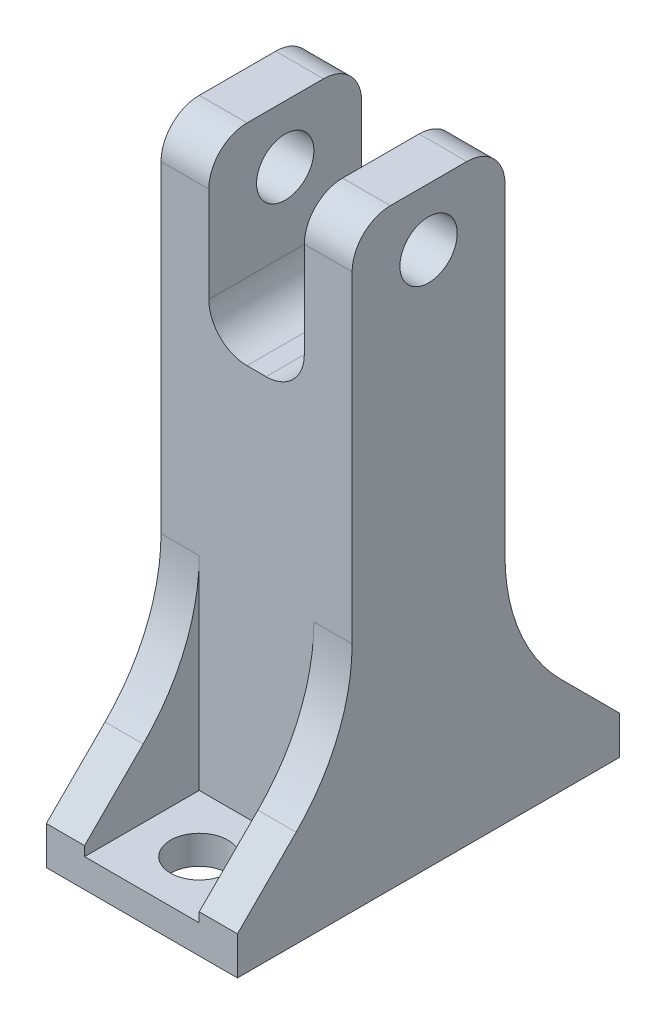
SolidWorks part; units mm, degrees
ref_plane "Front Plane" through (0, 0, 0) normal (0, 0, 1) x (1, 0, 0)
ref_plane "Top Plane" through (0, 0, 0) normal (0, 1, 0) x (1, 0, 0)
ref_plane "Right Plane" through (0, 0, 0) normal (1, 0, 0) x (0, 0, -1)
sketch "Sketch1" plane through (0, 0, 0) normal (0, 0, 1) x (1, 0, 0)
  line L0 (2.5, 15.5) -> (5, 15.5)
  line L1 (-5, -15.5) -> (5, -15.5)
  line L2 (-5, -15.5) -> (-5, 15.5)
  line L3 (-5, 15.5) -> (-2.5, 15.5)
  line L4 (5, -15.5) -> (5, 15.5)
  line L5 (-5, -15.5) -> (5, 15.5) construction
  line L6 (-5, 15.5) -> (5, -15.5) construction
  line L7 (-2.5, 6.5) -> (2.5, 6.5)
  line L8 (-2.5, 6.5) -> (-2.5, 15.5)
  line L10 (2.5, 6.5) -> (2.5, 15.5)
  line L11 (-2.5, 6.5) -> (2.5, 15.5) construction
  line L12 (-2.5, 15.5) -> (2.5, 6.5) construction
  point P0 (0, 0)
  point P5 (0, 11)
  dimension "D1" = 31
  dimension "D2" = 10
  dimension "D3" = 9
  dimension "D4" = 5
extrude "Boss-Extrude1" add sketch "Sketch1" along normal mid plane 8
sketch "Sketch2" plane through (5, 0, 0) normal (1, 0, 0) x (0, 0, -1)
  line L0 (0, 16.3044) -> (0, -16.984) construction
  line L1 (-4, 15.5) -> (4, 15.5) construction
  circle A0 centre (0, 12.5) radius 1.5
  point P6 (0, 0)
  dimension "D1" = 3
  dimension "D2" = 3
extrude "Cut-Extrude1" cut sketch "Sketch2" against normal through all
sketch "Sketch3" plane through (0, 0, 0) normal (1, 0, 0) x (0, 0, -1)
  line L0 (-4, -15.5) -> (-10, -15.5)
  line L1 (-4, -15.5) -> (-4, 15.5) construction
  line L2 (-10, -15.5) -> (-10, -13.5)
  line L3 (-4, -15.5) -> (4, -15.5) construction
  line L4 (-10, -13.5) -> (-4, -7.5)
  line L5 (0, 0) -> (0, -15.5) construction
  line L6 (-4, -7.5) -> (-4, -15.5)
  line L7 (4, -7.5) -> (4, -15.5)
  line L8 (10, -13.5) -> (4, -7.5)
  line L9 (10, -15.5) -> (10, -13.5)
  line L10 (4, -15.5) -> (10, -15.5)
  dimension "D1" = 6
  dimension "D2" = 2
  dimension "D3" = 8
extrude "Boss-Extrude2" add sketch "Sketch3" along normal mid plane 10
sketch "Sketch4" plane through (0, 0, 0) normal (0, 1, 0) x (1, 0, 0)
  line L0 (5, 4) -> (2.5, 4) construction
  line L1 (-3, 10) -> (3, 10)
  line L2 (-3, 10) -> (-3, 4)
  line L3 (-3, 4) -> (3, 4)
  line L4 (3, 10) -> (3, 4)
  line L5 (5, 10) -> (-5, 10) construction
  line L6 (0, 10.8803) -> (0, -10.8803) construction
  line L7 (-7.8361, 0) -> (6.6774, 0) construction
  line L8 (3, -10) -> (3, -4)
  line L9 (-3, -4) -> (3, -4)
  line L10 (-3, -10) -> (-3, -4)
  line L11 (-3, -10) -> (3, -10)
  point P10 (0, 10)
  point P15 (0, 0)
  dimension "D1" = 6
extrude "Cut-Extrude2" cut sketch "Sketch4" against normal blind 14
sketch "Sketch6" plane through (0, 0, 0) normal (0, 1, 0) x (1, 0, 0)
  line L0 (0, 12.7519) -> (0, -10) construction
  line L1 (-3, -10) -> (3, -10) construction
  line L2 (2.5, 4) -> (-2.5, 4) construction
  line L3 (-6.5793, 0) -> (6.8992, 0) construction
  line L4 (2.5, -4) -> (-2.5, -4) construction
  circle A0 centre (0, 7) radius 1.5
  circle A1 centre (0, -7) radius 1.5
  dimension "D1" = 3
  dimension "D3" = 3
  dimension "D2" = 3
extrude "Cut-Extrude3" cut sketch "Sketch6" against normal through all
fillet "Fillet1" radius 10 4 edges at (4, -7.5, -4) (-4, -7.5, -4) (4, -7.5, 4) (-4, -7.5, 4)
fillet "Fillet2" radius 2 2 edges at (2.5, 6.5, 0) (-2.5, 6.5, 0)
fillet "Fillet3" radius 2 4 edges at (-3.75, 15.5, -4) (3.75, 15.5, -4) (3.75, 15.5, 4) (-3.75, 15.5, 4)
